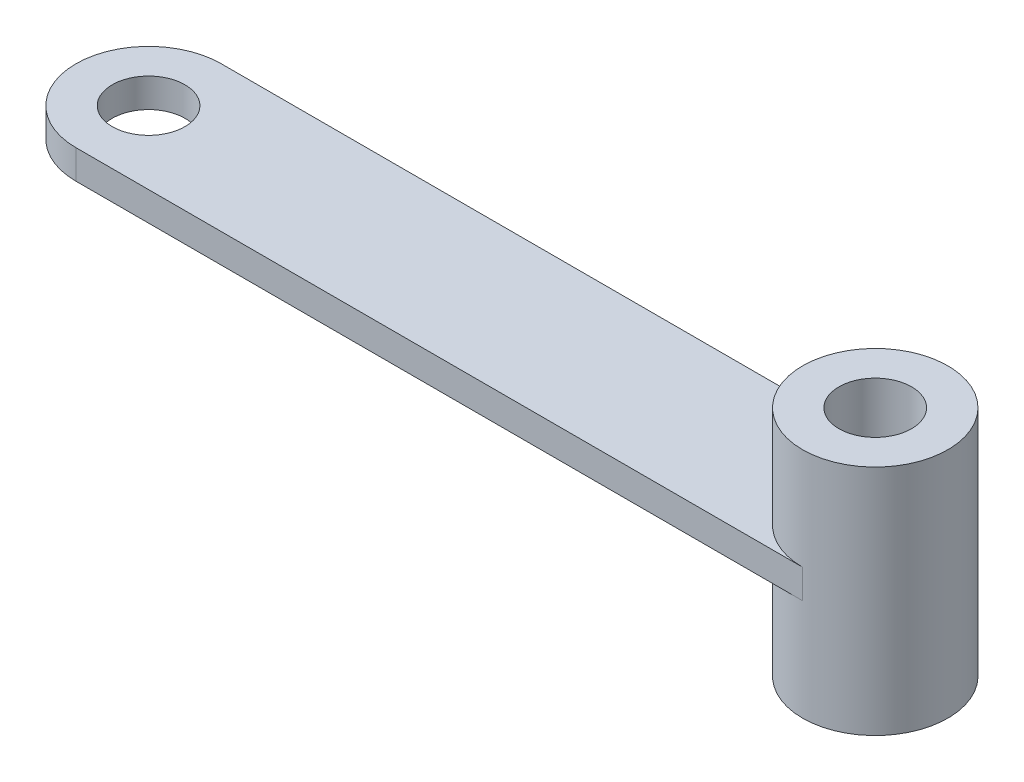
SolidWorks part; units mm, degrees
ref_plane "Front Plane" through (0, 0, 0) normal (0, 0, 1) x (1, 0, 0)
ref_plane "Top Plane" through (0, 0, 0) normal (0, 1, 0) x (1, 0, 0)
ref_plane "Right Plane" through (0, 0, 0) normal (1, 0, 0) x (0, 0, -1)
sketch "Sketch1" plane through (0, 0, 0) normal (0, 1, 0) x (1, 0, 0)
  line L0 (0, 0) -> (50, 0) construction
  line L1 (0, 5) -> (50, 5)
  line L2 (0, -5) -> (50, -5)
  arc A0 (0, 5) -> (0, -5) centre (0, 0) ccw
  arc A1 (50, -5) -> (50, 5) centre (50, 0) ccw
  circle A2 centre (0, 0) radius 2.5
  circle A3 centre (50, 0) radius 2.5
  point P3 (25, 0)
  dimension "D3" = 5
  dimension "D4" = 5
  dimension "D1" = 50
  dimension "D2" = 10
extrude "Boss-Extrude1" add sketch "Sketch1" along normal blind 2
ref_plane "Plane1" through (0, 1, 0) normal (0, 1, 0) x (1, 0, 0)
sketch "Sketch3" plane through (0, 1, 0) normal (0, 1, 0) x (1, 0, 0)
  circle A0 centre (50, 0) radius 5
  circle A1 centre (50, 0) radius 2.5
extrude "Boss-Extrude3" add sketch "Sketch3" along normal blind 8 and the other way blind 8
